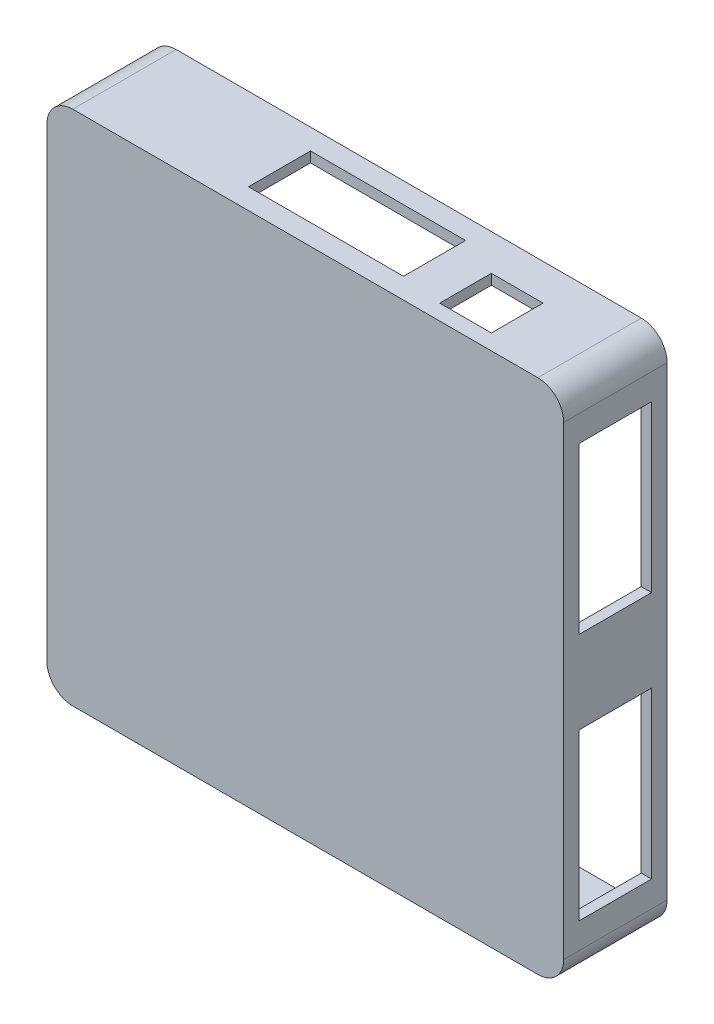
SolidWorks part; units mm, degrees
ref_plane "前视基准面" through (0, 0, 0) normal (0, 0, 1) x (1, 0, 0)
ref_plane "上视基准面" through (0, 0, 0) normal (0, 1, 0) x (1, 0, 0)
ref_plane "右视基准面" through (0, 0, 0) normal (1, 0, 0) x (0, 0, -1)
sketch "草图2" plane through (0, 0, 0) normal (0, 0, 1) x (1, 0, 0)
  line L1 (-50, -50) -> (50, -50)
  line L2 (-50, -50) -> (-50, 50)
  line L3 (-50, 50) -> (50, 50)
  line L4 (50, -50) -> (50, 50)
  line L5 (-50, -50) -> (50, 50) construction
  line L6 (-50, 50) -> (50, -50) construction
  point P0 (0, 0)
  dimension "D1" = 100
  dimension "D2" = 100
extrude "凸台-拉伸1" add sketch "草图2" along normal blind 20
sketch "草图3" plane through (0, 50, 0) normal (0, 1, 0) x (1, 0, 0)
  line L6 (50, -20) -> (50, 0) construction
  line L7 (23, -7) -> (33, -7)
  line L8 (23, -7) -> (23, -17)
  line L9 (23, -17) -> (33, -17)
  line L10 (33, -7) -> (33, -17)
  line L11 (23, -7) -> (33, -17) construction
  line L12 (23, -17) -> (33, -7) construction
  line L13 (50, -20) -> (-50, -20) construction
  point P0 (28, -12)
  dimension "D1" = 10
  dimension "D2" = 10
  dimension "D3" = 17
  dimension "D4" = 3
extrude "切除-拉伸1" cut sketch "草图3" against normal blind 12
sketch "草图4" plane through (0, 0, 0) normal (0, 0, -1) x (-1, 0, 0)
  line L1 (-48, -48) -> (48, -48)
  line L2 (-48, -48) -> (-48, 48)
  line L3 (-48, 48) -> (48, 48)
  line L4 (48, -48) -> (48, 48)
  line L5 (-48, -48) -> (48, 48) construction
  line L6 (-48, 48) -> (48, -48) construction
  point P0 (0, 0)
  dimension "D1" = 96
  dimension "D2" = 96
extrude "切除-拉伸2" cut sketch "草图4" against normal blind 17
sketch "草图5" plane through (0, 0, 17) normal (0, 0, -1) x (-1, 0, 0)
  line L1 (-41.25, -41.25) -> (41.25, -41.25)
  line L2 (-41.25, -41.25) -> (-41.25, 41.25)
  line L3 (-41.25, 41.25) -> (41.25, 41.25)
  line L4 (41.25, -41.25) -> (41.25, 41.25)
  line L5 (-41.25, -41.25) -> (41.25, 41.25) construction
  line L6 (-41.25, 41.25) -> (41.25, -41.25) construction
  line L7 (48, 48) -> (-23, 48) construction
  point P0 (0, 0)
  point P6 (0, 0)
  dimension "D1" = 82.5
  dimension "D2" = 82.5
  dimension "D3" = 6.75
extrude "切除-拉伸3" cut sketch "草图5" against normal blind 1
fillet "圆角1" radius 5 4 edges at (48, 48, 8.5) (-48, 48, 8.5) (-48, -48, 8.5) (48, -48, 8.5)
fillet "圆角2" radius 5 4 edges at (50, -50, 10) (50, 50, 10) (-50, 50, 10) (-50, -50, 10)
sketch "草图8" plane through (-50, 0, 0) normal (-1, 0, 0) x (0, 0, 1)
  line L1 (3, 40) -> (17, 40)
  line L2 (3, 40) -> (3, -40)
  line L3 (3, -40) -> (17, -40)
  line L4 (17, 40) -> (17, -40)
  line L5 (3, 40) -> (17, -40) construction
  line L6 (3, -40) -> (17, 40) construction
  line L8 (0, -45) -> (20, -45) construction
  line L10 (20, 45) -> (20, -45) construction
  line L11 (0, 45) -> (0, -45) construction
  line L13 (17, -8) -> (3, -8)
  line L14 (17, -8) -> (17, 8)
  line L15 (17, 8) -> (3, 8)
  line L16 (3, -8) -> (3, 8)
  line L17 (17, -8) -> (3, 8) construction
  line L18 (17, 8) -> (3, -8) construction
  point P0 (10, 0)
  point P11 (10, 0)
  point P16 (0, 0)
  dimension "D1" = 80
  dimension "D2" = 5
  dimension "D3" = 3
  dimension "D4" = 3
  dimension "D5" = 32
extrude "切除-拉伸4" cut sketch "草图8" against normal through all contours L4 L13 L2 L3 | L15 L4 L1 L2
sketch "草图9" plane through (0, -50, 0) normal (0, -1, 0) x (1, 0, 0)
  line L0 (0, 0) -> (0, 20) construction
  line L1 (-45, 20) -> (45, 20) construction
  line L2 (-45, 0) -> (45, 0) construction
  line L3 (-10, 17.5) -> (10, 17.5)
  line L4 (-10, 17.5) -> (-10, 2.5)
  line L5 (-10, 2.5) -> (10, 2.5)
  line L6 (10, 17.5) -> (10, 2.5)
  line L7 (-10, 17.5) -> (10, 2.5) construction
  line L8 (-10, 2.5) -> (10, 17.5) construction
  point P5 (0, 10)
  point P6 (0, 10)
  dimension "D1" = 20
  dimension "D2" = 2.5
extrude "切除-拉伸5" cut sketch "草图9" against normal blind 10
sketch "草图10" plane through (0, 50, 0) normal (0, 1, 0) x (1, 0, 0)
  line L0 (0, 0) -> (0, -20) construction
  line L1 (45, -20) -> (-45, -20) construction
  line L3 (-15, -16) -> (15, -16)
  line L4 (-15, -16) -> (-15, -4)
  line L5 (-15, -4) -> (15, -4)
  line L6 (15, -16) -> (15, -4)
  line L7 (-15, -16) -> (15, -4) construction
  line L8 (-15, -4) -> (15, -16) construction
  point P5 (0, -10)
  point P6 (0, -10)
  dimension "D1" = 30
  dimension "D2" = 12
extrude "切除-拉伸6" cut sketch "草图10" against normal blind 10
